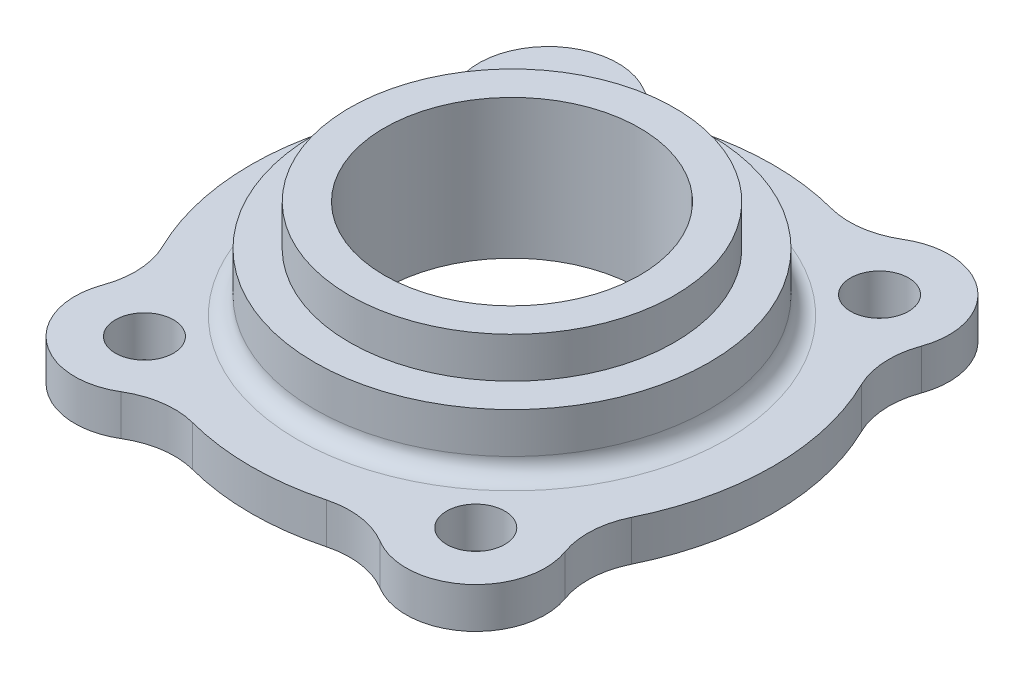
SolidWorks part; units mm, degrees
ref_plane "Front Plane" through (0, 0, 0) normal (0, 0, 1) x (1, 0, 0)
ref_plane "Top Plane" through (0, 0, 0) normal (0, 1, 0) x (1, 0, 0)
ref_plane "Right Plane" through (0, 0, 0) normal (1, 0, 0) x (0, 0, -1)
sketch "Sketch2" plane through (0, 0, 0) normal (0, 1, 0) x (1, 0, 0)
  circle A0 centre (0, 0) radius 11
  circle A1 centre (0, 0) radius 17
  circle A2 centre (0, 0) radius 14
  circle A3 centre (0, 0) radius 22.5
  dimension "D1" = 22
  dimension "D2" = 28
  dimension "D3" = 34
  dimension "D4" = 45
extrude "Boss-Extrude1" add sketch "Sketch2" along normal blind 12 contours A2 A0
sketch "Sketch3" plane through (0, 0, 0) normal (0, 1, 0) x (1, 0, 0)
  circle A0 centre (0, 0) radius 17
  circle A1 centre (0, 0) radius 14
extrude "Boss-Extrude2" add sketch "Sketch3" along normal blind 8.5
sketch "Sketch4" plane through (0, 0, 0) normal (0, 1, 0) x (1, 0, 0)
  line L0 (0, 36.6751) -> (0, 22.5) construction
  line L1 (0, -22.5) -> (0, -37.1671) construction
  arc A0 (-18.3611, 13.0046) -> (-18.3611, -13.0046) centre (0, 0) ccw
  arc A2 (-9.1668, 20.548) -> (-18.3611, 13.0046) centre (-14.2714, 17.3948) ccw
  arc A3 (18.3611, 13.0046) -> (9.1668, 20.548) centre (14.2714, 17.3948) ccw
  arc A4 (-18.3611, -13.0046) -> (-9.1668, -20.548) centre (-14.2714, -17.3948) ccw
  arc A5 (9.1668, -20.548) -> (18.3611, -13.0046) centre (14.2714, -17.3948) ccw
  circle A6 centre (0, 0) radius 22.5 construction
  arc A7 (-9.1668, -20.548) -> (9.1668, -20.548) centre (0, 0) ccw
  arc A8 (18.3611, -13.0046) -> (18.3611, 13.0046) centre (0, 0) ccw
  arc A9 (9.1668, 20.548) -> (-9.1668, 20.548) centre (0, 0) ccw
  circle A10 centre (-14.2714, 17.3948) radius 2.5
  circle A11 centre (14.2714, 17.3948) radius 2.5
  circle A12 centre (-14.2714, -17.3948) radius 2.5
  circle A13 centre (14.2714, -17.3948) radius 2.5
  circle A14 centre (0, 0) radius 17
  dimension "D1" = 12
  dimension "D2" = 12
  dimension "D3" = 12
  dimension "D4" = 12
  dimension "D6" = 28.5428
extrude "Boss-Extrude3" add sketch "Sketch4" along normal blind 3.5
fillet "Fillet1" radius 1.5 1 edges at (0, 3.5, 17)
fillet "Fillet2" radius 7 8 edges at (-9.1668, 1.75, 20.548) (9.1668, 1.75, 20.548) (9.1668, 1.75, -20.548) (-9.1668, 1.75, -20.548) (-18.3611, 1.75, 13.0046) (-18.3611, 1.75, -13.0046) (18.3611, 1.75, -13.0046) (18.3611, 1.75, 13.0046)
